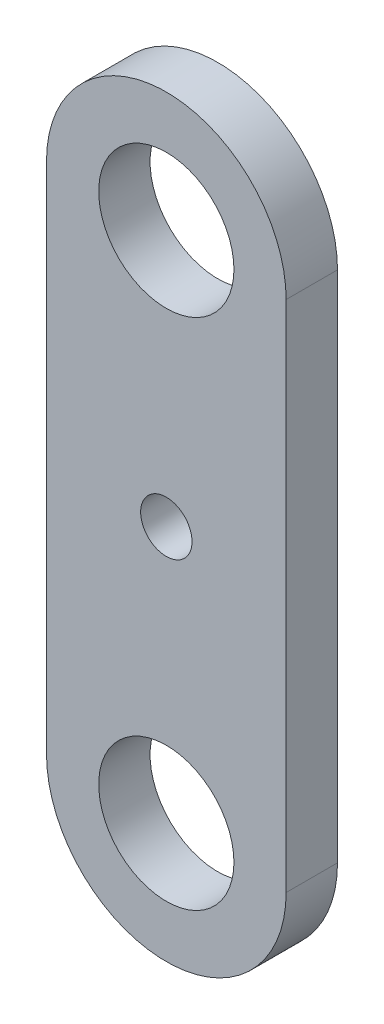
SolidWorks part; units mm, degrees
ref_plane "前视基准面" through (0, 0, 0) normal (0, 0, 1) x (1, 0, 0)
ref_plane "上视基准面" through (0, 0, 0) normal (0, 1, 0) x (1, 0, 0)
ref_plane "右视基准面" through (0, 0, 0) normal (1, 0, 0) x (0, 0, -1)
sketch "草图1" plane through (0, 0, 0) normal (0, 0, 1) x (1, 0, 0)
  line L0 (-7, 30) -> (-7, 0)
  line L1 (7, 0) -> (7, 30)
  circle A0 centre (0, 0) radius 3.95
  circle A1 centre (0, 30) radius 3.95
  circle A2 centre (0, 0) radius 7
  circle A3 centre (0, 30) radius 7
  circle A5 centre (0, 15) radius 1.5
  dimension "D1" = 7.9
  dimension "D2" = 14
  dimension "D4" = 7.9
  dimension "D3" = 30
  dimension "D5" = 15
extrude "凸台-拉伸1" add sketch "草图1" along normal blind 3 contours A3 A1 | A3 L0 A2 L1 A5 | A2 A0
